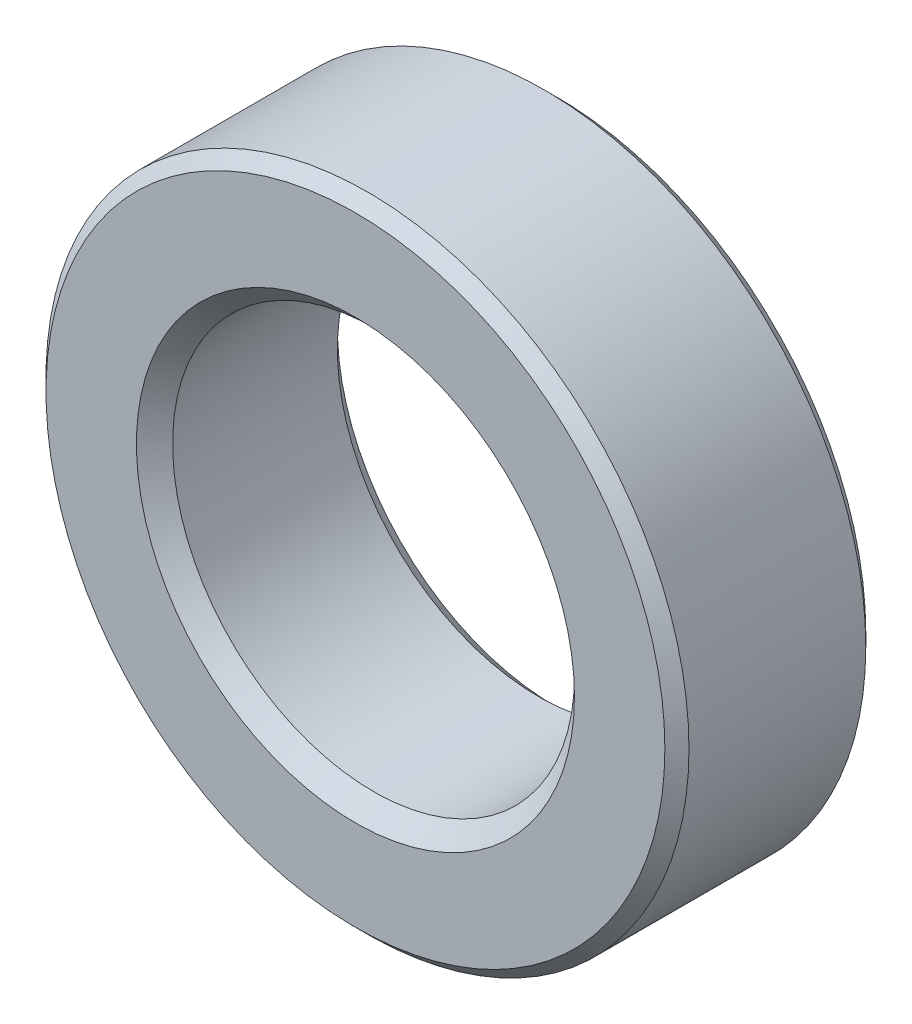
SolidWorks part; units mm, degrees
ref_plane "Front Plane" through (0, 0, 0) normal (0, 0, 1) x (1, 0, 0)
ref_plane "Top Plane" through (0, 0, 0) normal (0, 1, 0) x (1, 0, 0)
ref_plane "Right Plane" through (0, 0, 0) normal (1, 0, 0) x (0, 0, -1)
sketch "Sketch1" plane through (0, 0, 0) normal (0, 0, 1) x (1, 0, 0)
  circle A0 centre (0, 0) radius 8 construction
  circle A1 centre (0, 0) radius 5 construction
  point P4 (0, 8)
  dimension "ID" = 10
  dimension "OD" = 16
sketch "Sketch2" plane through (0, 0, 0) normal (1, 0, 0) x (0, 0, -1)
  line L0 (-2.5, 8) -> (2.5, 8) construction
  dimension "Length" = 5
sketch "Sketch3" plane through (0, 0, 0) normal (0, 0, 1) x (1, 0, 0)
  circle A0 centre (0, 0) radius 5 construction
  circle A1 centre (0, 0) radius 8 construction
  circle A2 centre (0, 0) radius 5
  circle A3 centre (0, 0) radius 8
extrude "Boss-Extrude1" add sketch "Sketch3" against normal up to vertex (2.5 mm away) and the other way up to vertex (2.5 mm away) up to point (0, 8, -2.5) other way up to point (0, 8, 2.5)
chamfer "Chamfer1" distance 0.3 angle 45 2 edges at (8, 0, 2.5) (8, 0, -2.5)
chamfer "Chamfer2" distance 0.45 angle 45 2 edges at (5, 0, 2.5) (5, 0, -2.5)
equation "\"D1@Chamfer1\"=(\"OD@Sketch1\"-\"ID@Sketch1\")*0.05"
equation "\"D1@Chamfer2\"=(\"OD@Sketch1\"-\"ID@Sketch1\")*0.075"
